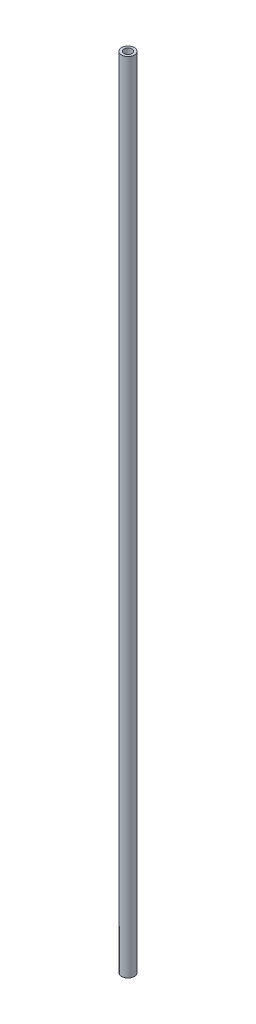
SolidWorks part; units mm, degrees
material "6063-T6"
ref_plane "Front Plane" through (0, 0, 0) normal (0, 0, 1) x (1, 0, 0)
ref_plane "Top Plane" through (0, 0, 0) normal (0, 1, 0) x (1, 0, 0)
ref_plane "Right Plane" through (0, 0, 0) normal (1, 0, 0) x (0, 0, -1)
sketch "Sketch1" plane through (0, 0, 0) normal (0, 1, 0) x (1, 0, 0)
  circle A0 centre (0, 0) radius 4
  circle A1 centre (0, 0) radius 2.5
  dimension "D1" = 8
  dimension "D2" = 1.5
extrude "Boss-Extrude1" add sketch "Sketch1" along normal blind 495
thread "Thread1" pitch 1.5 start angle 0, offset 0.0001, length 20, pitch 1.5, diameter 10
ref_plane "Plane1" through (5, 0.0001, 0) normal (0, 0, 1) x (1, 0, 0)
sketch "Thread Profile1" plane through (5, 0.0001, 0) normal (0, 0, 1) x (1, 0, 0)
  line L0 (0, 0) -> (0, 1.5) construction
  line L11 (0, 0) -> (0, 1.3125)
  line L12 (0, 1.3125) -> (-0.8119, 0.8437)
  line L13 (-0.8119, 0.8437) -> (-0.8119, 0.4687)
  line L15 (-0.8119, 0.4687) -> (0, 0)
  line L17 (-0.8119, 0.6562) -> (0, 0.6562) construction
  point P2 (0, 0)
  dimension "Pitch" = 1.5
  dimension "Profile_Angle" = 60
  dimension "Profile_Land" = 0.375
  dimension "Profile_Height" = 0.8119
